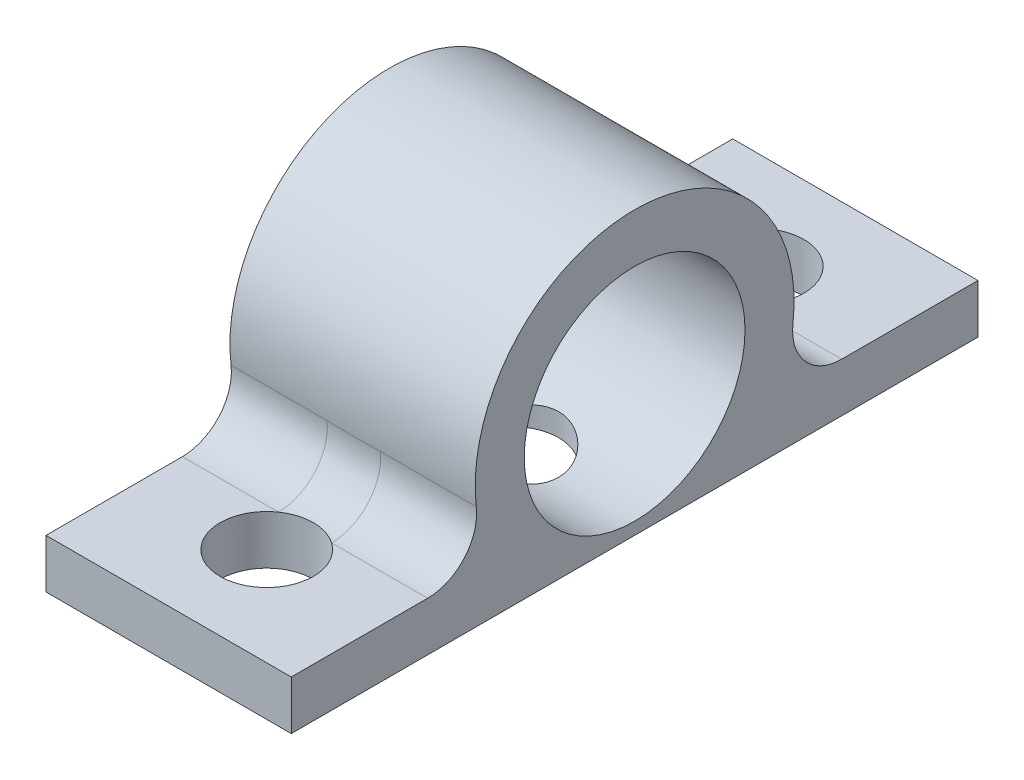
SolidWorks part; units mm, degrees
ref_plane "Front Plane" through (0, 0, 0) normal (0, 0, 1) x (1, 0, 0)
ref_plane "Top Plane" through (0, 0, 0) normal (0, 1, 0) x (1, 0, 0)
ref_plane "Right Plane" through (0, 0, 0) normal (1, 0, 0) x (0, 0, -1)
sketch "Sketch1" plane through (0, 0, 0) normal (1, 0, 0) x (0, 0, -1)
  line L1 (0, 0) -> (28, 0)
  line L2 (0, 0) -> (0, 2)
  line L3 (0, 2) -> (8.2337, 2)
  line L4 (28, 0) -> (28, 2)
  line L11 (7.5, 0) -> (20.5, 0)
  line L17 (19.7663, 2) -> (28, 2)
  circle A0 centre (14, 5) radius 4.5
  arc A1 (19.7663, 2) -> (8.2337, 2) centre (14, 5) ccw
  circle A2 centre (14, 5) radius 6.5 construction
  point P12 (0, 0)
  dimension "D2" = 28
  dimension "D3" = 2
  dimension "D5" = 2
extrude "Boss-Extrude1" add sketch "Sketch1" along normal blind 10
sketch "Sketch2" plane through (0, 2, 0) normal (0, 1, 0) x (1, 0, 0)
  line L0 (5, 24) -> (5, 4) construction
  line L2 (10, 0) -> (0, 0) construction
  line L6 (10, 0) -> (10, 28) construction
  circle A0 centre (5, 24) radius 1.9
  circle A1 centre (5, 4) radius 1.9
  point P8 (0, 0)
  point P11 (5, 0)
  point P15 (10, 14)
  point P16 (5, 14)
  dimension "D2" = 3.8
  dimension "D1" = 20
extrude "Cut-Extrude1" cut sketch "Sketch2" against normal blind 10
fillet "Fillet1" radius 2 2 edges at (5, 2, -19.7663) (5, 2, -8.2337)
sketch "Sketch3" plane through (0, 0, 0) normal (0, -1, 0) x (1, 0, 0)
  line L0 (10, 0) -> (10, -28) construction
  line L1 (10, -28) -> (0, -28) construction
  circle A0 centre (5, -14) radius 1.9
  point P4 (10, -14)
  point P7 (5, -28)
  dimension "D1" = 3.8
extrude "Cut-Extrude2" cut sketch "Sketch3" against normal blind 5
